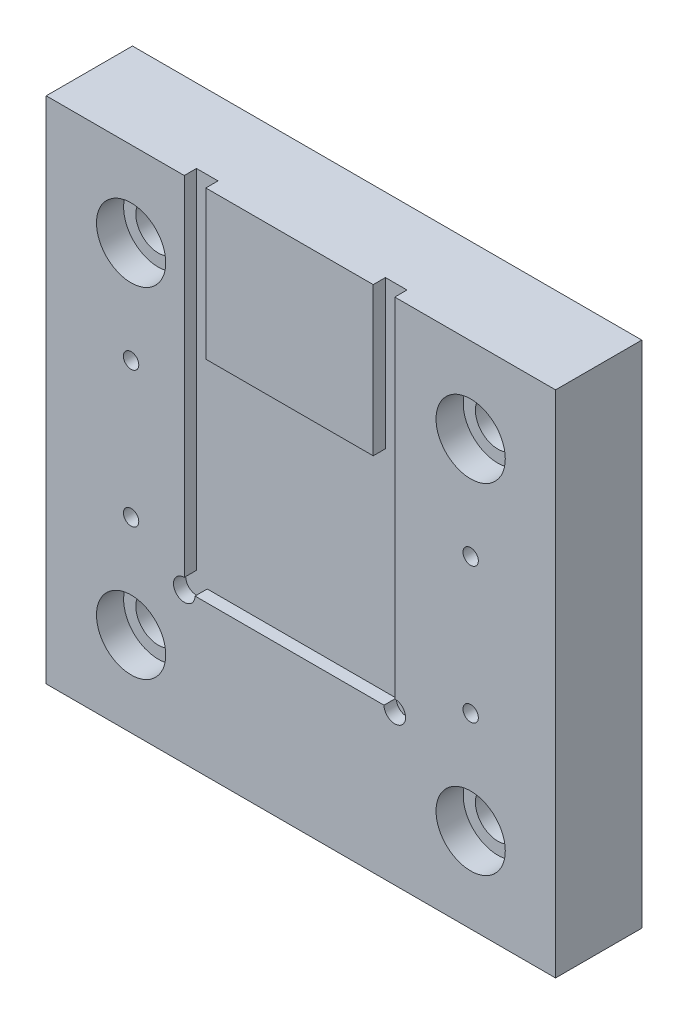
SolidWorks part; units mm, degrees
material "Copper"
ref_plane "Front Plane" through (0, 0, 0) normal (0, 0, 1) x (1, 0, 0)
ref_plane "Top Plane" through (0, 0, 0) normal (0, 1, 0) x (1, 0, 0)
ref_plane "Right Plane" through (0, 0, 0) normal (1, 0, 0) x (0, 0, -1)
sketch "Sketch1" plane through (0, 0, 0) normal (0, 0, 1) x (1, 0, 0)
  line L1 (-73.1662, 61.0295) -> (1.8338, 61.0295)
  line L2 (-73.1662, 61.0295) -> (-73.1662, -13.9705)
  line L3 (-73.1662, -13.9705) -> (1.8338, -13.9705)
  line L4 (1.8338, 61.0295) -> (1.8338, -13.9705)
  line L5 (-73.1662, 61.0295) -> (1.8338, -13.9705) construction
  line L6 (-73.1662, -13.9705) -> (1.8338, 61.0295) construction
  circle A0 centre (-60.6662, -1.4705) radius 3.3
  circle A1 centre (-10.6662, -1.4705) radius 3.3
  circle A2 centre (-10.6662, 48.5295) radius 3.3
  circle A3 centre (-60.6662, 48.5295) radius 3.3
  circle A4 centre (-60.6662, 33.5295) radius 1.1303
  circle A5 centre (-10.6662, 33.5295) radius 1.1303
  circle A6 centre (-60.6662, 13.5295) radius 1.1303
  circle A7 centre (-10.6662, 13.5295) radius 1.1303
  point P0 (-35.6662, 23.5295)
  dimension "D7" = 12.5
  dimension "D10" = 12.5
  dimension "D14" = 2.2606
  dimension "D15" = 2.2606
  dimension "D16" = 2.2606
  dimension "D17" = 2.2606
  dimension "D1" = 75
  dimension "D2" = 75
  dimension "D3" = 50
  dimension "D4" = 50
  dimension "D5" = 50
  dimension "D6" = 50
  dimension "D8" = 12.5
  dimension "D9" = 12.5
  dimension "D11" = 12.5
  dimension "D12" = 27.5
  dimension "D13" = 27.5
  dimension "D18" = 20
  dimension "D19" = 20
  dimension "D20" = 12.5
extrude "Boss-Extrude1" add sketch "Sketch1" along normal blind 12.7
sketch "Sketch2" plane through (0, 0, 12.7) normal (0, 0, 1) x (1, 0, 0)
  circle A0 centre (-60.6662, 48.5295) radius 5.1
  circle A1 centre (-10.6662, 48.5295) radius 5.1
  circle A2 centre (-60.6662, -1.4705) radius 5.1
  circle A3 centre (-10.6662, -1.4705) radius 5.1
  dimension "D1" = 10.2
  dimension "D2" = 10.2
  dimension "D3" = 10.2
  dimension "D4" = 10.2
extrude "Cut-Extrude1" cut sketch "Sketch2" against normal blind 4
sketch "Sketch3" plane through (0, 0, 12.7) normal (0, 0, 1) x (1, 0, 0)
  line L0 (1.8338, 61.0295) -> (-73.1662, 61.0295) construction
  line L1 (-49.6638, 39.194) -> (-25.0138, 39.194)
  line L2 (-52.8388, 39.194) -> (-52.8388, 9.7815)
  line L3 (-51.2513, 8.194) -> (-23.4263, 8.194)
  line L4 (-21.8388, 39.194) -> (-21.8388, 9.7815)
  line L6 (-52.8388, 39.194) -> (-52.8388, 61.0295)
  line L7 (-52.8388, 61.0295) -> (-49.6638, 61.0295)
  line L8 (-49.6638, 39.194) -> (-49.6638, 61.0295)
  line L11 (-25.0138, 39.194) -> (-25.0138, 61.0295)
  line L13 (-25.0138, 61.0295) -> (-21.8388, 61.0295)
  line L14 (-21.8388, 39.194) -> (-21.8388, 61.0295)
  arc A0 (-52.8388, 9.7815) -> (-51.2513, 8.194) centre (-52.8388, 8.194) ccw
  arc A3 (-23.4263, 8.194) -> (-21.8388, 9.7815) centre (-21.8388, 8.194) ccw
  dimension "D5" = 21.8354
  dimension "D7" = 3.175
  dimension "D8" = 3.175
  dimension "D1" = 31
  dimension "D2" = 31
  dimension "D3" = 3.175
  dimension "D4" = 3.175
  dimension "D11" = 31
extrude "Cut-Extrude2" cut sketch "Sketch3" against normal blind 1.8
equation "\"D1@Sketch1\"=75"
equation "\"D2@Sketch1\"=\"D1@Sketch1\""
equation "\"D5@Sketch1\"=\"D4@Sketch1\""
equation "\"D6@Sketch1\"=\"D3@Sketch1\""
equation "\"D4@Sketch1\"=\"D3@Sketch1\""
equation "\"D9@Sketch1\"=\"D7@Sketch1\""
equation "\"D10@Sketch1\"=\"D7@Sketch1\""
equation "\"D11@Sketch1\"=\"D7@Sketch1\""
equation "\"D13@Sketch1\"=\"D12@Sketch1\""
equation "\"D2@Sketch2\"=\"D1@Sketch2\""
equation "\"D3@Sketch2\"=\"D1@Sketch2\""
equation "\"D4@Sketch2\"=\"D1@Sketch2\""
equation "\"D16@Sketch1\"=\"D14@Sketch1\""
equation "\"D17@Sketch1\"=\"D15@Sketch1\""
equation "\"D19@Sketch1\"=20"
